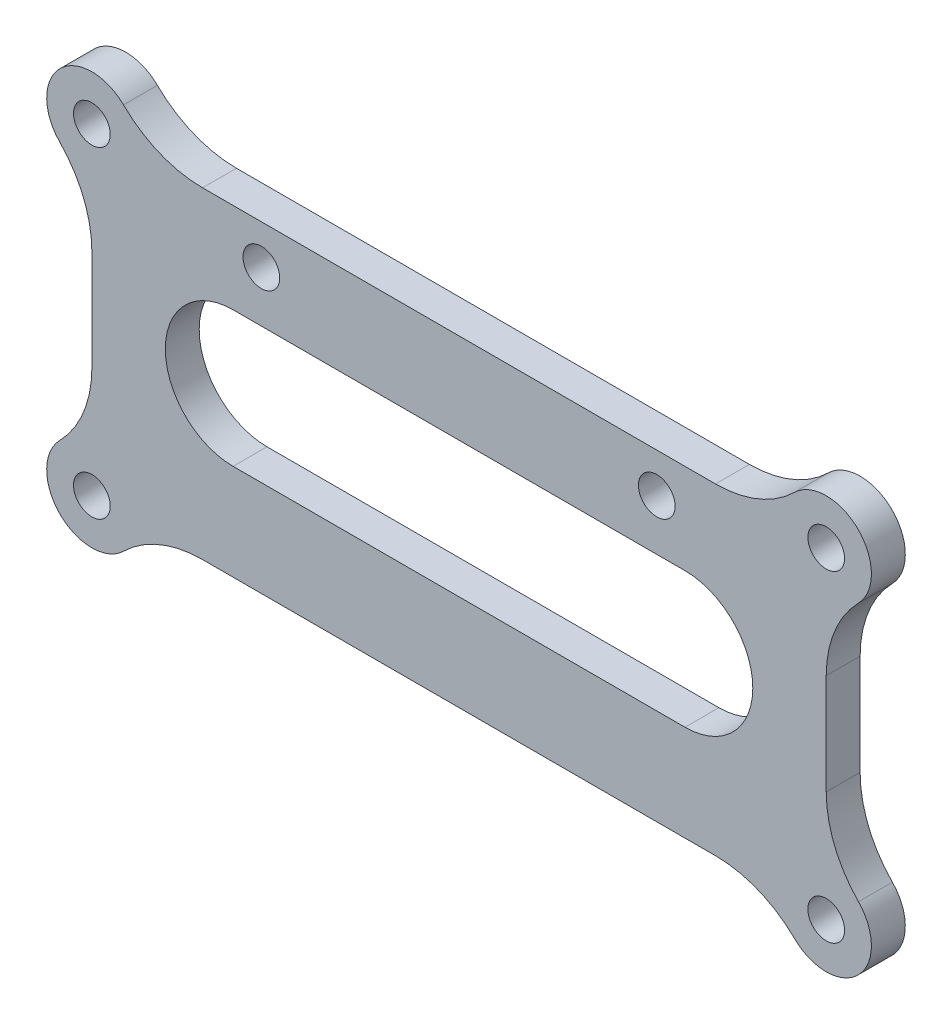
SolidWorks part; units mm, degrees
material "ABS"
ref_plane "Спереди" through (0, 0, 0) normal (0, 0, 1) x (1, 0, 0)
ref_plane "Сверху" through (0, 0, 0) normal (0, 1, 0) x (1, 0, 0)
ref_plane "Справа" through (0, 0, 0) normal (1, 0, 0) x (0, 0, -1)
sketch "Эскиз1" plane through (0, 0, 0) normal (0, 0, 1) x (1, 0, 0)
  line L0 (-32.5, 0) -> (32.5, 0)
  line L3 (-32.5, 28.5) -> (32.5, 28.5)
  line L4 (32.5, 0) -> (32.5, 28.5)
  line L6 (-32.5, 28.5) -> (0, 0) construction
  line L7 (-32.5, 0) -> (-32.5, 28.5)
  line L8 (0, 0) -> (32.5, 28.5) construction
  circle A0 centre (-32.5, 28.5) radius 1.625
  arc A1 (-28.5, 28.5) -> (-32.5, 24.5) centre (-32.5, 28.5) ccw
  circle A2 centre (32.5, 28.5) radius 1.625
  arc A3 (32.5, 24.5) -> (28.5, 28.5) centre (32.5, 28.5) ccw
  arc A8 (-30.2165, -39.7842) -> (-30.0697, -39.6771) centre (-32.5, -36.5) ccw [skipped]
  arc A9 (-30.8963, -36.7625) -> (-30.8944, -36.7501) centre (-32.5, -36.5) ccw [skipped]
  arc A10 (34.8906, -39.707) -> (34.7835, -39.7842) centre (32.5, -36.5) ccw [skipped]
  arc A11 (34.1056, -36.7501) -> (34.1094, -36.7244) centre (32.5, -36.5) ccw [skipped]
  circle A12 centre (-32.5, 0) radius 1.625
  arc A13 (-32.5, 4) -> (-28.5, 0) centre (-32.5, 0) ccw
  arc A14 (28.5, 0) -> (32.5, 4) centre (32.5, 0) ccw
  circle A15 centre (32.5, 0) radius 1.625
  point P0 (0, 0)
  point P20 (0, -4)
  dimension "D2" = 3.25
  dimension "D3" = 8
  dimension "D8" = 3.25
  dimension "D9" = 8
  dimension "D10" = 3.25
  dimension "D11" = 8
  dimension "D1" = 28.5
  dimension "D5" = 65
  dimension "D6" = 32.5
  dimension "D7" = 90
  dimension "D4" = 4
extrude "Бобышка-Вытянуть1" add sketch "Эскиз1" along normal blind 3
fillet "Скругление1" radius 10 8 edges at (-28.5, 28.5, 1.5) (28.5, 28.5, 1.5) (32.5, 24.5, 1.5) (-32.5, 24.5, 1.5) (32.5, 4, 1.5) (28.5, 0, 1.5) (-28.5, 0, 1.5) (-32.5, 4, 1.5)
sketch "Эскиз3" plane through (0, 0, 0) normal (0, 0, -1) x (-1, 0, 0)
  line L0 (0, 28.5) -> (0, -32.5) construction
  line L1 (22.702, 28.5) -> (-22.702, 28.5) construction
  line L3 (-31.8936, 25) -> (26.7306, 25) construction
  circle A0 centre (-17.5, 25) radius 1.625
  circle A1 centre (17.5, 25) radius 1.625
  dimension "D1" = 3.25
  dimension "D2" = 17.5
  dimension "D3" = 25
extrude "Вырез-Вытянуть1" cut sketch "Эскиз3" against normal blind 10
sketch "Эскиз4" plane through (0, 0, 3) normal (0, 0, 1) x (1, 0, 0)
  line L0 (0, 28.5) -> (0, 0) construction
  line L1 (8.65, 14.3) -> (21.15, 14.3)
  line L2 (24.4, 11.05) -> (24.4, 8.95)
  line L3 (21.15, 5.7) -> (8.65, 5.7)
  line L4 (-8.65, 14.05) -> (-21.15, 14.05)
  line L5 (-8.45, 6.15) -> (-8.45, 13.85)
  line L6 (-21.15, 5.95) -> (-8.65, 5.95)
  line L7 (-24.15, 11.05) -> (-24.15, 8.95)
  line L8 (-8.65, 14.05) -> (-21.15, 14.05)
  line L9 (-8.45, 6.15) -> (-8.45, 13.85)
  line L10 (-21.15, 5.95) -> (-8.65, 5.95)
  line L11 (-24.15, 11.05) -> (-24.15, 8.95)
  line L12 (-8.2, 6.15) -> (-8.2, 13.85)
  line L13 (-21.15, 5.7) -> (-8.65, 5.7)
  line L14 (-24.4, 11.05) -> (-24.4, 8.95)
  line L15 (-8.65, 14.3) -> (-21.15, 14.3)
  line L16 (-8.2, 6.15) -> (-8.2, 13.85)
  line L17 (-21.15, 5.7) -> (-8.65, 5.7)
  line L18 (-24.4, 11.05) -> (-24.4, 8.95)
  line L19 (-8.65, 14.3) -> (-21.15, 14.3)
  line L20 (-22.702, 0) -> (22.702, 0)
  line L21 (32.5, 9.798) -> (32.5, 18.702)
  line L22 (22.702, 28.5) -> (-22.702, 28.5)
  line L23 (-32.5, 18.702) -> (-32.5, 9.798)
  line L24 (-22.702, 0) -> (22.702, 0)
  line L25 (32.5, 9.798) -> (32.5, 18.702)
  line L26 (22.702, 28.5) -> (-22.702, 28.5)
  line L27 (-32.5, 18.702) -> (-32.5, 9.798)
  line L28 (8.2, 6.15) -> (8.2, 13.85)
  line L29 (24.15, 11.05) -> (24.15, 8.95)
  line L30 (21.15, 5.95) -> (8.65, 5.95)
  line L31 (8.45, 6.15) -> (8.45, 13.85)
  line L32 (8.65, 14.05) -> (21.15, 14.05)
  arc A0 (8.2, 13.85) -> (8.65, 14.3) centre (8.65, 13.85) cw
  arc A1 (21.15, 14.3) -> (24.4, 11.05) centre (21.15, 11.05) cw
  arc A2 (24.4, 8.95) -> (21.15, 5.7) centre (21.15, 8.95) cw
  arc A3 (8.65, 5.7) -> (8.2, 6.15) centre (8.65, 6.15) cw
  arc A4 (-8.45, 13.85) -> (-8.65, 14.05) centre (-8.65, 13.85) ccw
  arc A5 (-8.65, 5.95) -> (-8.45, 6.15) centre (-8.65, 6.15) ccw
  arc A6 (-24.15, 8.95) -> (-21.15, 5.95) centre (-21.15, 8.95) ccw
  arc A7 (-21.15, 14.05) -> (-24.15, 11.05) centre (-21.15, 11.05) ccw
  arc A8 (-8.45, 13.85) -> (-8.65, 14.05) centre (-8.65, 13.85) ccw
  arc A9 (-8.65, 5.95) -> (-8.45, 6.15) centre (-8.65, 6.15) ccw
  arc A10 (-24.15, 8.95) -> (-21.15, 5.95) centre (-21.15, 8.95) ccw
  arc A11 (-21.15, 14.05) -> (-24.15, 11.05) centre (-21.15, 11.05) ccw
  arc A12 (-8.65, 5.7) -> (-8.2, 6.15) centre (-8.65, 6.15) ccw
  arc A13 (-24.4, 8.95) -> (-21.15, 5.7) centre (-21.15, 8.95) ccw
  arc A14 (-21.15, 14.3) -> (-24.4, 11.05) centre (-21.15, 11.05) ccw
  arc A15 (-8.2, 13.85) -> (-8.65, 14.3) centre (-8.65, 13.85) ccw
  arc A16 (-8.65, 5.7) -> (-8.2, 6.15) centre (-8.65, 6.15) ccw
  arc A17 (-24.4, 8.95) -> (-21.15, 5.7) centre (-21.15, 8.95) ccw
  arc A18 (-21.15, 14.3) -> (-24.4, 11.05) centre (-21.15, 11.05) ccw
  arc A19 (-8.2, 13.85) -> (-8.65, 14.3) centre (-8.65, 13.85) ccw
  arc A20 (21.15, 14.05) -> (24.15, 11.05) centre (21.15, 11.05) cw
  arc A21 (24.15, 8.95) -> (21.15, 5.95) centre (21.15, 8.95) cw
  arc A22 (8.65, 5.95) -> (8.45, 6.15) centre (8.65, 6.15) cw
  arc A23 (8.45, 13.85) -> (8.65, 14.05) centre (8.65, 13.85) cw
  arc A28 (29.7006, -2.8571) -> (22.702, 0) centre (22.702, -10) ccw
  arc A29 (29.7006, -2.8571) -> (35.3571, 2.7994) centre (32.5, 0) ccw
  arc A30 (32.5, 9.798) -> (35.3571, 2.7994) centre (42.5, 9.798) ccw
  arc A31 (35.3571, 25.7006) -> (32.5, 18.702) centre (42.5, 18.702) ccw
  arc A32 (35.3571, 25.7006) -> (29.7006, 31.3571) centre (32.5, 28.5) ccw
  arc A33 (22.702, 28.5) -> (29.7006, 31.3571) centre (22.702, 38.5) ccw
  arc A34 (-29.7006, 31.3571) -> (-22.702, 28.5) centre (-22.702, 38.5) ccw
  arc A35 (-29.7006, 31.3571) -> (-35.3571, 25.7006) centre (-32.5, 28.5) ccw
  arc A36 (-32.5, 18.702) -> (-35.3571, 25.7006) centre (-42.5, 18.702) ccw
  arc A37 (-35.3571, 2.7994) -> (-32.5, 9.798) centre (-42.5, 9.798) ccw
  arc A38 (-35.3571, 2.7994) -> (-29.7006, -2.8571) centre (-32.5, 0) ccw
  arc A39 (-22.702, 0) -> (-29.7006, -2.8571) centre (-22.702, -10) ccw
  arc A40 (29.7006, -2.8571) -> (22.702, 0) centre (22.702, -10) ccw
  arc A41 (29.7006, -2.8571) -> (35.3571, 2.7994) centre (32.5, 0) ccw
  arc A42 (32.5, 9.798) -> (35.3571, 2.7994) centre (42.5, 9.798) ccw
  arc A43 (35.3571, 25.7006) -> (32.5, 18.702) centre (42.5, 18.702) ccw
  arc A44 (35.3571, 25.7006) -> (29.7006, 31.3571) centre (32.5, 28.5) ccw
  arc A45 (22.702, 28.5) -> (29.7006, 31.3571) centre (22.702, 38.5) ccw
  arc A46 (-29.7006, 31.3571) -> (-22.702, 28.5) centre (-22.702, 38.5) ccw
  arc A47 (-29.7006, 31.3571) -> (-35.3571, 25.7006) centre (-32.5, 28.5) ccw
  arc A48 (-32.5, 18.702) -> (-35.3571, 25.7006) centre (-42.5, 18.702) ccw
  arc A49 (-35.3571, 2.7994) -> (-32.5, 9.798) centre (-42.5, 9.798) ccw
  arc A50 (-35.3571, 2.7994) -> (-29.7006, -2.8571) centre (-32.5, 0) ccw
  arc A51 (-22.702, 0) -> (-29.7006, -2.8571) centre (-22.702, -10) ccw
  dimension "D1" = 0
  dimension "D2" = 0
  dimension "D3" = 0
extrude "Вырез-Вытянуть2" [suppressed] cut sketch "Эскиз4" against normal blind 10 contours L16 A19 L19 A18 L18 A17 L17 A16 A11 L8 A8 L9 A9 L10 A10 L11 | A3 L3 A2 L2 A1 L1 A0 L28 L31 A23 L32 A20 L29 A21 L30 A22
sketch "Эскиз5" plane through (0, 0, 0) normal (0, 0, -1) x (-1, 0, 0)
  circle A1 centre (26.6, 10) radius 1.625
  circle A2 centre (26.6, 10) radius 1.625
  circle A3 centre (-26.6, 10) radius 1.625
  circle A4 centre (-26.6, 10) radius 1.625
  circle A5 centre (-6, 10) radius 1.625
  circle A6 centre (-6, 10) radius 1.625
  circle A7 centre (6, 10) radius 1.625
  circle A8 centre (6, 10) radius 1.625
  dimension "D1" = 0
  dimension "D2" = 0
  dimension "D3" = 0
  dimension "D4" = 0
extrude "Вырез-Вытянуть3" [suppressed] cut sketch "Эскиз5" against normal blind 10
sketch "Эскиз8" plane through (0, 0, 0) normal (0, 0, -1) x (-1, 0, 0)
  line L0 (0, 28.5) -> (0, 0) construction
  line L1 (22.702, 28.5) -> (-22.702, 28.5) construction
  line L2 (-20, 14.5) -> (20, 14.5) construction
  line L3 (-20, 20.5) -> (20, 20.5)
  line L4 (-20, 8.5) -> (20, 8.5)
  arc A0 (-20, 20.5) -> (-20, 8.5) centre (-20, 14.5) ccw
  arc A1 (20, 8.5) -> (20, 20.5) centre (20, 14.5) ccw
  point P7 (0, 14.5)
  dimension "D1" = 40
  dimension "D2" = 12
  dimension "D3" = 8
extrude "Вырез-Вытянуть4" cut sketch "Эскиз8" against normal blind 10
